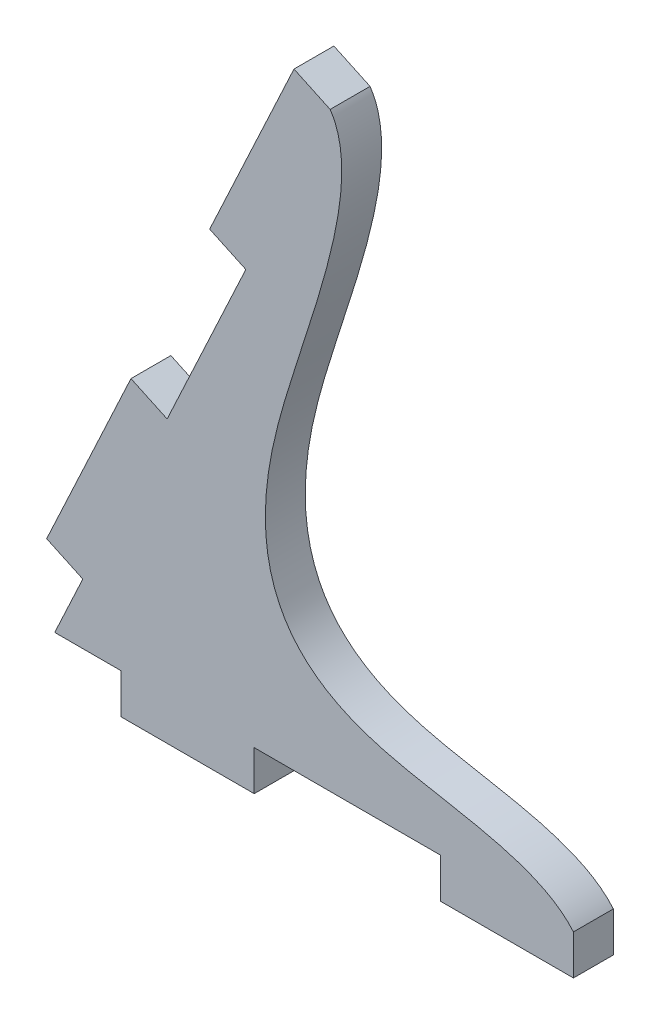
SolidWorks part; units mm, degrees
ref_plane "Alzado" through (0, 0, 0) normal (0, 0, 1) x (1, 0, 0)
ref_plane "Planta" through (0, 0, 0) normal (0, 1, 0) x (1, 0, 0)
ref_plane "Vista lateral" through (0, 0, 0) normal (1, 0, 0) x (0, 0, -1)
sketch "Croquis1" plane through (0, 0, 0) normal (0, 0, 1) x (1, 0, 0)
  line L0 (20.7083, 44.4091) -> (0, 0)
  line L1 (2.1131, 4.5315) -> (8.4524, 18.1262)
  line L2 (5, 0) -> (15, 0)
  line L3 (5, 0) -> (5, -3)
  line L4 (5, -3) -> (15, -3)
  line L5 (15, 0) -> (15, -3)
  line L6 (39, 0) -> (29, 0)
  line L7 (39, 0) -> (39, -3)
  line L8 (39, -3) -> (29, -3)
  line L9 (29, 0) -> (29, -3)
  line L10 (2.1131, 4.5315) -> (-0.6058, 5.7994)
  line L11 (8.4524, 18.1262) -> (5.7334, 19.394)
  line L12 (-0.6058, 5.7994) -> (5.7334, 19.394)
  line L13 (20.7083, 44.4091) -> (14.369, 30.8145)
  line L14 (39, 0) -> (0, 0)
  line L15 (20.7083, 44.4091) -> (17.9894, 45.6769)
  line L16 (14.369, 30.8145) -> (11.6501, 32.0823)
  line L17 (17.9894, 45.6769) -> (11.6501, 32.0823)
  spline S2 degree 3 poles (39, 0) (36.4021, 3.088) (28.2161, 3.5153) (17.8173, 6.8834) (14.4644, 12.4949) (18.1112, 27.508) (23.3616, 40.5643) (20.7083, 44.4091) knots 0 0 0 0 0.279354 0.353116 0.694897 0.763858 1 1 1 1
  point P11 (5, -1.5)
  dimension "D1" = 65
  dimension "D2" = 49
  dimension "D3" = 39
  dimension "D4" = 3
  dimension "D5" = 3
  dimension "D6" = 15
  dimension "D7" = 15
  dimension "D8" = 10
  dimension "D9" = 10
  dimension "D10" = 5
  dimension "D11" = 5
extrude "Saliente-Extruir1" add sketch "Croquis1" along normal blind 3 contours L6 S2 L0 L14 L2 | L12 L10 L0 L11 | L15 L17 L16 L0 | L5 L2 L3 L4 | L6 L9 L8 L7
